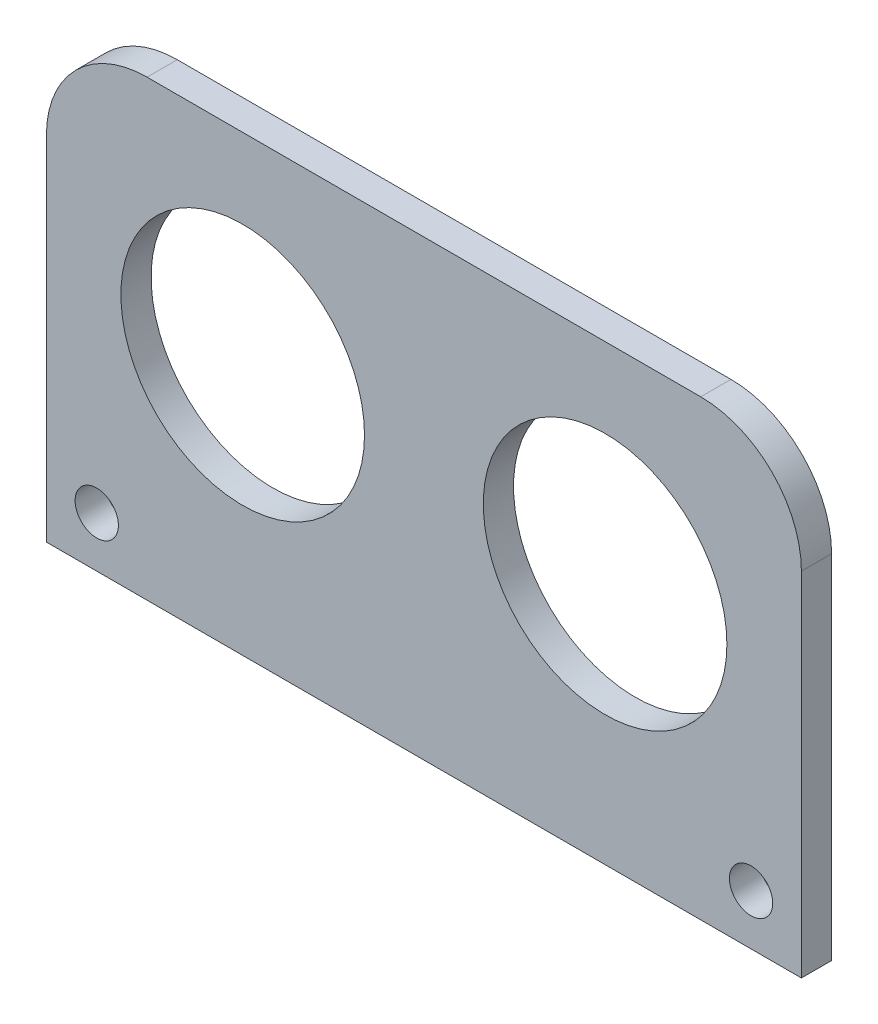
SolidWorks part; units mm, degrees
material "5052-H34"
ref_plane "正面" through (0, 0, 0) normal (0, 0, 1) x (1, 0, 0)
ref_plane "平面" through (0, 0, 0) normal (0, 1, 0) x (1, 0, 0)
ref_plane "右側面" through (0, 0, 0) normal (1, 0, 0) x (0, 0, -1)
sketch "ｽｹｯﾁ1" plane through (0, 0, 0) normal (0, 0, 1) x (1, 0, 0)
  line L0 (19.5, 25) -> (19.5, 34.5) construction
  line L1 (0, 0) -> (75, 0)
  line L2 (0, 0) -> (0, 45)
  line L3 (0, 45) -> (75, 45)
  line L4 (75, 0) -> (75, 45)
  line L5 (19.5, 25) -> (55.5, 25) construction
  line L6 (37.5, 45) -> (37.5, 0) construction
  circle A0 centre (19.5, 25) radius 12.1
  circle A5 centre (55.5, 25) radius 12.1
  circle A6 centre (5, 5) radius 2.15
  circle A7 centre (70, 5) radius 2.15
  point P15 (19.5, 25)
  point P17 (37.5, 25)
  dimension "D1" = 24.2
  dimension "D4" = 24.2
  dimension "D9" = 4.3
  dimension "D2" = 9.5
  dimension "D5" = 45
  dimension "D6" = 75
  dimension "D7" = 25
  dimension "D8" = 36
  dimension "D10" = 5
  dimension "D11" = 5
extrude "ﾎﾞｽ - 押し出し1" add sketch "ｽｹｯﾁ1" along normal blind 3
fillet "ﾌｨﾚｯﾄ1" radius 10 2 edges at (0, 45, 1.5) (75, 45, 1.5)
